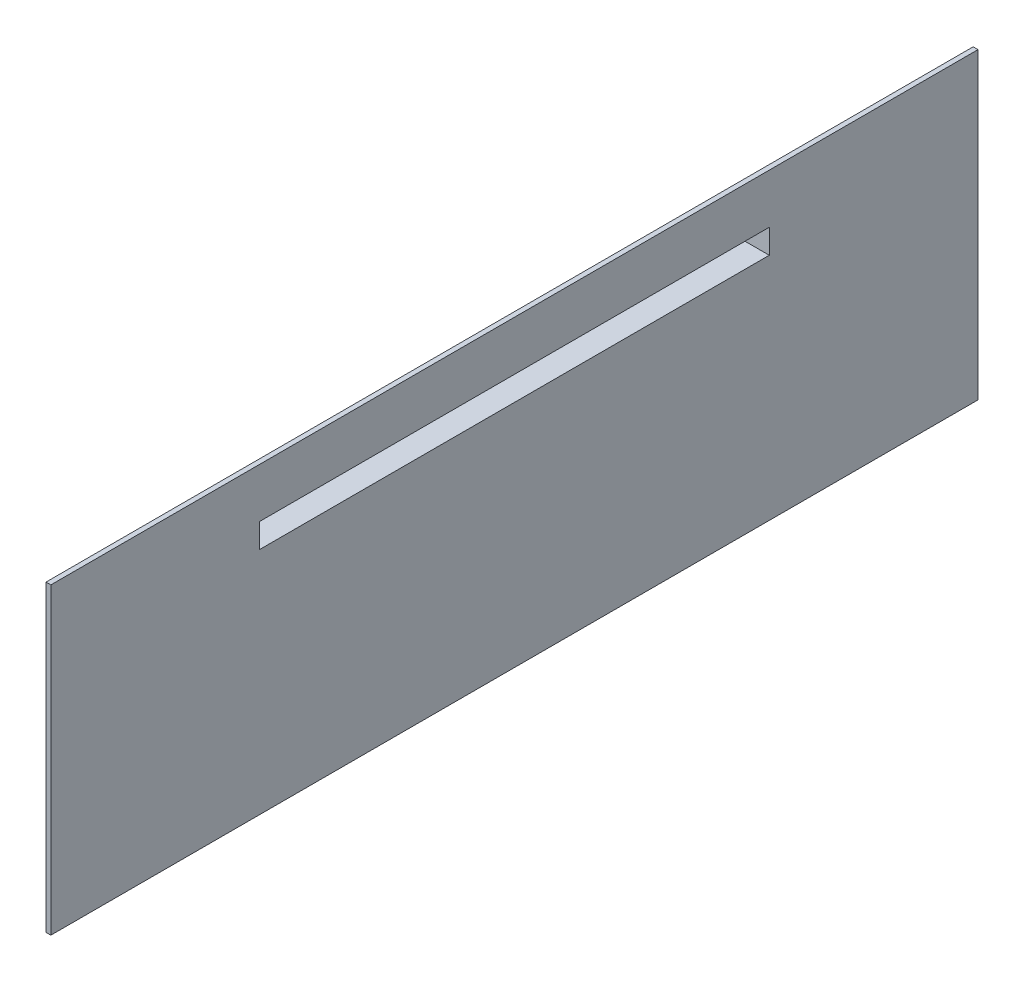
SolidWorks part; units mm, degrees
ref_plane "Front Plane" through (0, 0, 0) normal (0, 0, 1) x (1, 0, 0)
ref_plane "Top Plane" through (0, 0, 0) normal (0, 1, 0) x (1, 0, 0)
ref_plane "Right Plane" through (0, 0, 0) normal (1, 0, 0) x (0, 0, -1)
ref_plane "Plane1" through (532, 0, 0) normal (-1, 0, 0) x (0, -1, 0)
sketch "Sketch1" plane through (532, 0, 0) normal (-1, 0, 0) x (0, -1, 0)
  line L0 (75, 0) -> (-50, 0)
  line L1 (-50, 0) -> (-50, -382)
  line L2 (-50, -382) -> (75, -382)
  line L3 (75, -382) -> (75, 0)
  dimension "D1" = 125
  dimension "D2" = 382
extrude "Boss-Extrude1" add sketch "Sketch1" against normal blind 2
sketch "Sketch2" plane through (532, 0, 0) normal (-1, 0, 0) x (0, 0, 1)
  line L0 (-83, 32.6137) -> (-83, 16.6137)
  line L1 (-83, 16.6137) -> (-299, 16.6137)
  line L2 (-299, 16.6137) -> (-299, 32.6137)
  line L3 (-299, 32.6137) -> (-83, 32.6137)
  line L4 (0, -75) -> (0, 50) construction
  dimension "D1" = 83
extrude "Boss-Extrude2" add sketch "Sketch2" along normal blind 10
sketch "Sketch3" plane through (522, 0, 0) normal (-1, 0, 0) x (0, 0, 1)
  line L0 (-296, 29.6137) -> (-296, 19.6137)
  line L1 (-296, 19.6137) -> (-86, 19.6137)
  line L2 (-86, 19.6137) -> (-86, 29.6137)
  line L3 (-86, 29.6137) -> (-296, 29.6137)
  line L9 (0, -75) -> (0, 50) construction
  dimension "D1" = 86
extrude "Cut-Extrude1" cut sketch "Sketch3" against normal through all
